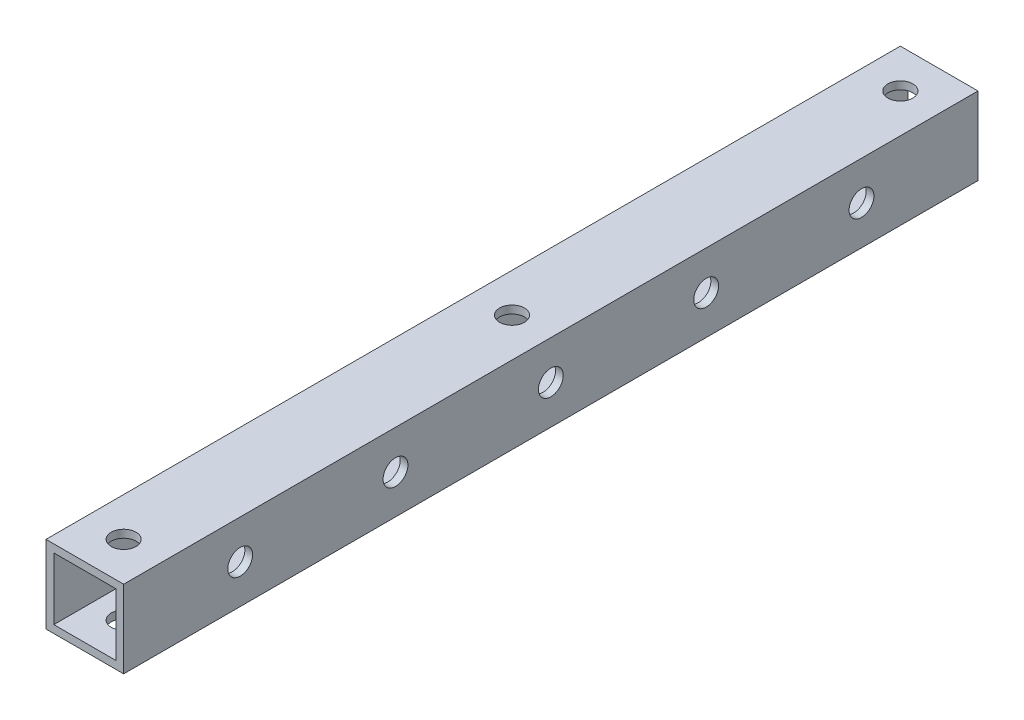
SolidWorks part; units mm, degrees
ref_plane "Front Plane" through (0, 0, 0) normal (0, 0, 1) x (1, 0, 0)
ref_plane "Top Plane" through (0, 0, 0) normal (0, 1, 0) x (1, 0, 0)
ref_plane "Right Plane" through (0, 0, 0) normal (1, 0, 0) x (0, 0, -1)
sketch "Sketch1" plane through (0, 0, 0) normal (0, 0, 1) x (1, 0, 0)
  line L1 (-31.5217, 15.2174) -> (-21.5217, 15.2174)
  line L2 (-31.5217, 15.2174) -> (-31.5217, 5.2174)
  line L3 (-31.5217, 5.2174) -> (-21.5217, 5.2174)
  line L4 (-21.5217, 15.2174) -> (-21.5217, 5.2174)
  dimension "D1" = 10
  dimension "D2" = 10
extrude "Boss-Extrude1" add sketch "Sketch1" along normal blind 55
sketch "Sketch2" plane through (0, 0, 55) normal (0, 0, 1) x (1, 0, 0)
  line L5 (-30.5174, 14.2131) -> (-22.5174, 14.2131)
  line L6 (-30.5174, 14.2131) -> (-30.5174, 6.2131)
  line L7 (-30.5174, 6.2131) -> (-22.5174, 6.2131)
  line L8 (-22.5174, 14.2131) -> (-22.5174, 6.2131)
  dimension "D1" = 8
  dimension "D2" = 8
extrude "Cut-Extrude1" cut sketch "Sketch2" against normal blind 110
sketch "Sketch3" plane through (0, 15.2174, 0) normal (0, 1, 0) x (1, 0, 0)
  line L0 (-21.5217, 0) -> (-31.5217, 0) construction
  line L1 (-21.5217, -55) -> (-31.5217, -55) construction
  circle A0 centre (-26.5217, -5) radius 1.6
  circle A1 centre (-26.5217, -55) radius 1.6
  line M4 (-31.5217, -55) -> (-21.5217, -55)
  dimension "D1" = 5
sketch "Sketch4" plane through (-21.5217, 0, 0) normal (1, 0, 0) x (0, 0, -1)
  line L0 (0, 5.2174) -> (0, 15.2174) construction
  line L1 (-55, 5.2174) -> (-55, 15.2174) construction
  circle A0 centre (-15, 10.2174) radius 1.6
  circle A1 centre (-35, 10.2174) radius 1.6
  circle A2 centre (-55, 10.2174) radius 1.6
  dimension "D1" = 15
  dimension "D2" = 20
extrude "Cut-Extrude2" cut sketch "Sketch4" against normal blind 10
extrude "Cut-Extrude3" cut sketch "Sketch3" against normal blind 10 contours A1 M4 | A0
mirror "Mirror1" about plane through (0, 0, 55) normal (0, 0, 1) of "Cut-Extrude1", "Boss-Extrude1", "Cut-Extrude2", "Cut-Extrude3"
